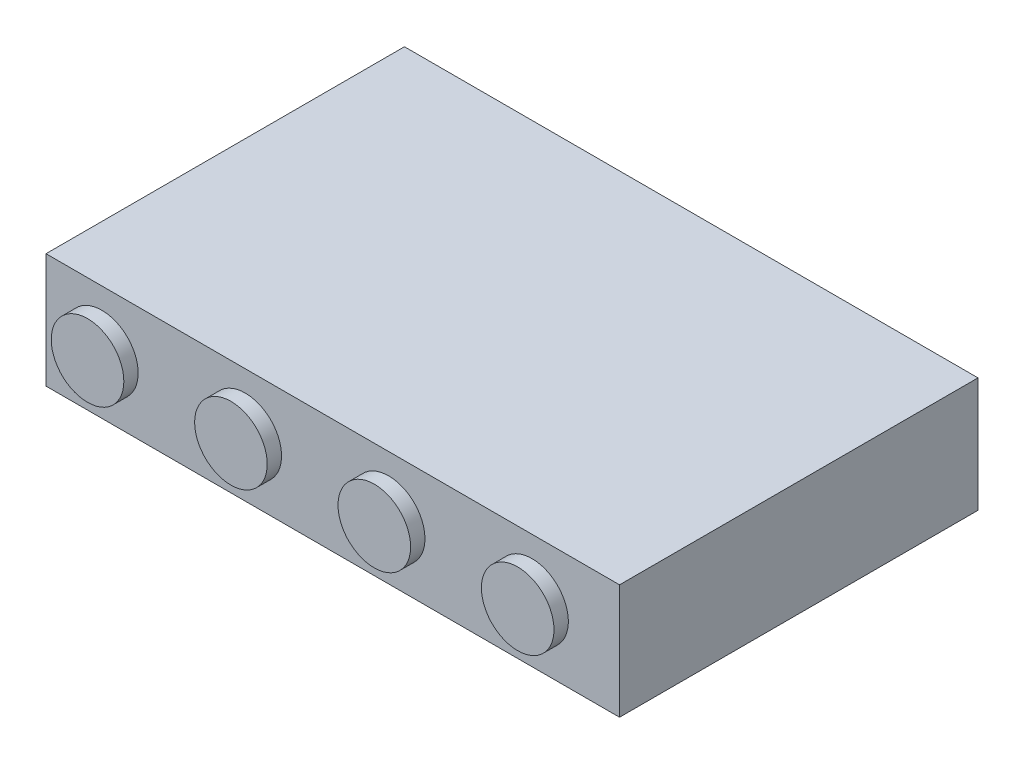
SolidWorks part; units mm, degrees
ref_plane "前视基准面" through (0, 0, 0) normal (0, 0, 1) x (1, 0, 0)
ref_plane "上视基准面" through (0, 0, 0) normal (0, 1, 0) x (1, 0, 0)
ref_plane "右视基准面" through (0, 0, 0) normal (1, 0, 0) x (0, 0, -1)
sketch "草图1" plane through (0, 0, 0) normal (0, 1, 0) x (1, 0, 0)
  line L1 (-189.3617, 111.9681) -> (210.6383, 111.9681)
  line L2 (-189.3617, 111.9681) -> (-189.3617, -138.0319)
  line L3 (-189.3617, -138.0319) -> (210.6383, -138.0319)
  line L4 (210.6383, 111.9681) -> (210.6383, -138.0319)
  dimension "D1" = 400
  dimension "D2" = 250
extrude "凸台-拉伸1" add sketch "草图1" along normal blind 80
sketch "草图3" plane through (0, 0, -111.9681) normal (0, 0, -1) x (-1, 0, 0)
  line L0 (-210.6383, 40) -> (189.3617, 40) construction
  line L1 (-210.6383, 80) -> (-210.6383, 0) construction
  line L2 (189.3617, 80) -> (189.3617, 0) construction
  circle A0 centre (-10.6383, 40) radius 26.348
extrude "凸台-拉伸2" add sketch "草图3" along normal blind 10
sketch "草图2" plane through (0, 0, 138.0319) normal (0, 0, 1) x (1, 0, 0)
  line L0 (-189.3617, 40) -> (210.6383, 40) construction
  line L1 (-189.3617, 80) -> (-189.3617, 0) construction
  line L2 (210.6383, 80) -> (210.6383, 0) construction
  circle A0 centre (-150.3906, 40) radius 25.3091
  circle A1 centre (-50.3906, 40) radius 25.3091
  circle A2 centre (49.6094, 40) radius 25.3091
  circle A3 centre (149.6094, 40) radius 25.3091
  dimension "D1" = 4
extrude "凸台-拉伸3" add sketch "草图2" along normal blind 10
